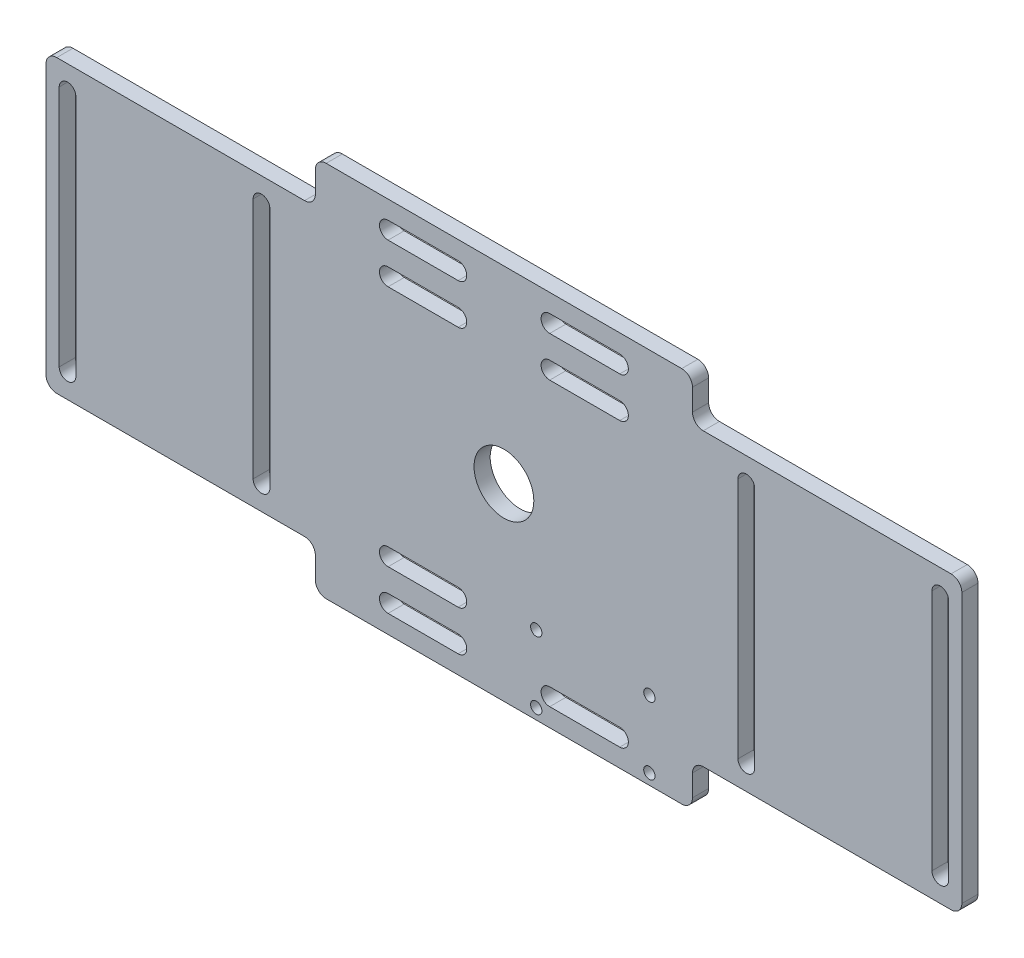
SolidWorks part; units mm, degrees
ref_plane "前基準面" through (0, 0, 0) normal (0, 0, 1) x (1, 0, 0)
ref_plane "上基準面" through (0, 0, 0) normal (0, 1, 0) x (1, 0, 0)
ref_plane "右基準面" through (0, 0, 0) normal (1, 0, 0) x (0, 0, -1)
sketch "草圖1" plane through (0, 0, 0) normal (0, 0, 1) x (1, 0, 0)
  line L1 (-85, 35) -> (85, 35)
  line L2 (-85, 35) -> (-85, -35)
  line L3 (-85, -35) -> (85, -35)
  line L4 (85, 35) -> (85, -35)
  line L5 (-85, 35) -> (85, -35) construction
  line L6 (-85, -35) -> (85, 35) construction
  point P0 (0, 0)
  dimension "D1" = 170
  dimension "D2" = 70
extrude "填料-伸長1" add sketch "草圖1" along normal blind 3
sketch "草圖2" plane through (0, 0, 3) normal (0, 0, 1) x (1, 0, 0)
  line L0 (-1000, 0) -> (49000, 0) construction
  line L1 (45, -986.1952) -> (45, 49013.8048) construction
  line L2 (-81, -962.7943) -> (-81, 49037.2057) construction
  line L3 (45, -22.5) -> (45, 22.5) construction
  line L4 (43.45, -22.5) -> (43.45, 22.5)
  line L5 (46.55, -22.5) -> (46.55, 22.5)
  line L6 (-45, -1000) -> (-45, 49000) construction
  line L7 (-45, -22.5) -> (-45, 22.5) construction
  line L8 (-46.55, -22.5) -> (-46.55, 22.5)
  line L9 (-43.45, -22.5) -> (-43.45, 22.5)
  line L10 (0, -1000) -> (0, 49000) construction
  line L11 (-1010.5287, 30) -> (48989.4713, 30) construction
  line L12 (-1007.193, -30) -> (48992.807, -30) construction
  line L13 (21.5, -30) -> (8.5, -30) construction
  line L16 (6, -996.0597) -> (6, 49003.9403) construction
  line L19 (81, -968.4295) -> (81, 49031.5705) construction
  line L20 (-81, -22.5) -> (-81, 22.5) construction
  line L21 (-82.55, -22.5) -> (-82.55, 22.5)
  line L22 (-79.45, -22.5) -> (-79.45, 22.5)
  line L23 (81, -22.5) -> (81, 22.5) construction
  line L24 (79.45, -22.5) -> (79.45, 22.5)
  line L25 (82.55, -22.5) -> (82.55, 22.5)
  line L26 (27, -997.4467) -> (27, 49002.5533) construction
  line L27 (-1014.4971, -33) -> (48985.5029, -33) construction
  line L28 (-1015.8254, -20.5) -> (48984.1746, -20.5) construction
  line L29 (-85, -35) -> (85, -35) construction
  line L30 (21.5, -31.6) -> (8.5, -31.6)
  line L33 (21.5, -28.4) -> (8.5, -28.4)
  line L34 (-21.5, -30) -> (-8.5, -30) construction
  line L35 (-21.5, -31.6) -> (-8.5, -31.6)
  line L36 (-21.5, -28.4) -> (-8.5, -28.4)
  line L37 (21.5, 30) -> (8.5, 30) construction
  line L38 (21.5, 31.6) -> (8.5, 31.6)
  line L39 (21.5, 28.4) -> (8.5, 28.4)
  line L40 (-21.5, 30) -> (-8.5, 30) construction
  line L41 (-21.5, 31.6) -> (-8.5, 31.6)
  line L42 (-21.5, 28.4) -> (-8.5, 28.4)
  line L43 (21.5, 22.5) -> (8.5, 22.5) construction
  line L44 (21.5, 24.1) -> (8.5, 24.1)
  line L45 (21.5, 20.9) -> (8.5, 20.9)
  line L46 (-21.5, 22.5) -> (-8.5, 22.5) construction
  line L47 (-21.5, 24.1) -> (-8.5, 24.1)
  line L48 (-21.5, 20.9) -> (-8.5, 20.9)
  line L49 (-21.5, -22.5) -> (-8.5, -22.5) construction
  line L50 (-21.5, -24.1) -> (-8.5, -24.1)
  line L51 (-21.5, -20.9) -> (-8.5, -20.9)
  arc A0 (43.45, -22.5) -> (46.55, -22.5) centre (45, -22.5) ccw
  arc A1 (46.55, 22.5) -> (43.45, 22.5) centre (45, 22.5) ccw
  arc A2 (-46.55, -22.5) -> (-43.45, -22.5) centre (-45, -22.5) ccw
  arc A3 (-43.45, 22.5) -> (-46.55, 22.5) centre (-45, 22.5) ccw
  arc A12 (-82.55, -22.5) -> (-79.45, -22.5) centre (-81, -22.5) ccw
  arc A13 (-79.45, 22.5) -> (-82.55, 22.5) centre (-81, 22.5) ccw
  arc A14 (79.45, -22.5) -> (82.55, -22.5) centre (81, -22.5) ccw
  arc A15 (82.55, 22.5) -> (79.45, 22.5) centre (81, 22.5) ccw
  circle A16 centre (0, 0) radius 5.55
  circle A17 centre (27, -20.5) radius 1.05
  circle A18 centre (6, -20.5) radius 1.05
  circle A19 centre (6, -33) radius 1.05
  circle A20 centre (27, -33) radius 1.05
  arc A23 (21.5, -31.6) -> (21.5, -28.4) centre (21.5, -30) ccw
  arc A24 (8.5, -28.4) -> (8.5, -31.6) centre (8.5, -30) ccw
  arc A25 (-21.5, -31.6) -> (-21.5, -28.4) centre (-21.5, -30) cw
  arc A26 (-8.5, -28.4) -> (-8.5, -31.6) centre (-8.5, -30) cw
  arc A27 (21.5, 31.6) -> (21.5, 28.4) centre (21.5, 30) cw
  arc A28 (8.5, 28.4) -> (8.5, 31.6) centre (8.5, 30) cw
  arc A29 (-21.5, 31.6) -> (-21.5, 28.4) centre (-21.5, 30) ccw
  arc A30 (-8.5, 28.4) -> (-8.5, 31.6) centre (-8.5, 30) ccw
  arc A31 (21.5, 24.1) -> (21.5, 20.9) centre (21.5, 22.5) cw
  arc A32 (8.5, 20.9) -> (8.5, 24.1) centre (8.5, 22.5) cw
  arc A33 (-21.5, 24.1) -> (-21.5, 20.9) centre (-21.5, 22.5) ccw
  arc A34 (-8.5, 20.9) -> (-8.5, 24.1) centre (-8.5, 22.5) ccw
  arc A35 (-21.5, -24.1) -> (-21.5, -20.9) centre (-21.5, -22.5) cw
  arc A36 (-8.5, -20.9) -> (-8.5, -24.1) centre (-8.5, -22.5) cw
  point P9 (45, 0)
  point P16 (-45, 0)
  point P31 (15, -30)
  point P47 (-81, 0)
  point P54 (81, 0)
  point P72 (-15, -30)
  point P81 (15, 30)
  point P88 (-15, 30)
  point P97 (15, 22.5)
  point P102 (-15, 22.5)
  point P110 (-15, -22.5)
  dimension "D10" = 1.6
  dimension "D20" = 11.1
  dimension "D21" = 2.1
  dimension "D2" = 45
  dimension "D3" = 3.1
  dimension "D4" = 90
  dimension "D5" = 45
  dimension "D6" = 3.1
  dimension "D7" = 45
  dimension "D8" = 60
  dimension "D9" = 30
  dimension "D11" = 13
  dimension "D12" = 12.5
  dimension "D13" = 21
  dimension "D14" = 162
  dimension "D15" = 81
  dimension "D16" = 3.1
  dimension "D17" = 45
  dimension "D18" = 45
  dimension "D19" = 3.1
  dimension "D22" = 2
  dimension "D23" = 6
  dimension "D24" = 8.5
  dimension "D25" = 2
  dimension "D26" = 2
extrude "除料-伸長1" cut sketch "草圖2" against normal through all
sketch "草圖4" plane through (0, 0, 3) normal (0, 0, 1) x (1, 0, 0)
  line L0 (85, -35) -> (85, 35) construction
  line L1 (85, 35) -> (35, 35)
  line L2 (85, 35) -> (85, 27)
  line L3 (83, 27) -> (37, 27)
  line L4 (35, 33) -> (35, 29)
  line L5 (85, 35) -> (-85, 35) construction
  line L6 (-103.8053, 0) -> (147.3737, 0) construction
  line L7 (33, 35) -> (35, 35)
  line L8 (85, 27) -> (85, 25)
  line L9 (0, 92.8328) -> (0, -104.1404) construction
  line L10 (85, -27) -> (85, -25)
  line L11 (33, -35) -> (35, -35)
  line L12 (35, -33) -> (35, -29)
  line L13 (83, -27) -> (37, -27)
  line L14 (85, -35) -> (85, -27)
  line L15 (85, -35) -> (35, -35)
  line L16 (-85, -35) -> (-35, -35)
  line L17 (-85, -35) -> (-85, -27)
  line L18 (-83, -27) -> (-37, -27)
  line L19 (-35, -33) -> (-35, -29)
  line L20 (-33, -35) -> (-35, -35)
  line L21 (-85, -27) -> (-85, -25)
  line L22 (-85, 27) -> (-85, 25)
  line L23 (-33, 35) -> (-35, 35)
  line L24 (-35, 33) -> (-35, 29)
  line L25 (-83, 27) -> (-37, 27)
  line L26 (-85, 35) -> (-85, 27)
  line L27 (-85, 35) -> (-35, 35)
  arc A0 (85, 25) -> (83, 27) centre (83, 25) ccw
  arc A1 (37, 27) -> (35, 29) centre (37, 29) cw
  arc A2 (35, 33) -> (33, 35) centre (33, 33) ccw
  arc A3 (35, -33) -> (33, -35) centre (33, -33) cw
  arc A4 (37, -27) -> (35, -29) centre (37, -29) ccw
  arc A5 (85, -25) -> (83, -27) centre (83, -25) cw
  arc A6 (-85, -25) -> (-83, -27) centre (-83, -25) ccw
  arc A7 (-37, -27) -> (-35, -29) centre (-37, -29) cw
  arc A8 (-35, -33) -> (-33, -35) centre (-33, -33) ccw
  arc A9 (-35, 33) -> (-33, 35) centre (-33, 33) cw
  arc A10 (-37, 27) -> (-35, 29) centre (-37, 29) ccw
  arc A11 (-85, 25) -> (-83, 27) centre (-83, 25) cw
  dimension "D3" = 2
  dimension "D4" = 2
  dimension "D5" = 2
  dimension "D1" = 8
  dimension "D2" = 50
  dimension "D6" = 2
extrude "除料-伸長2" cut sketch "草圖4" against normal through all
